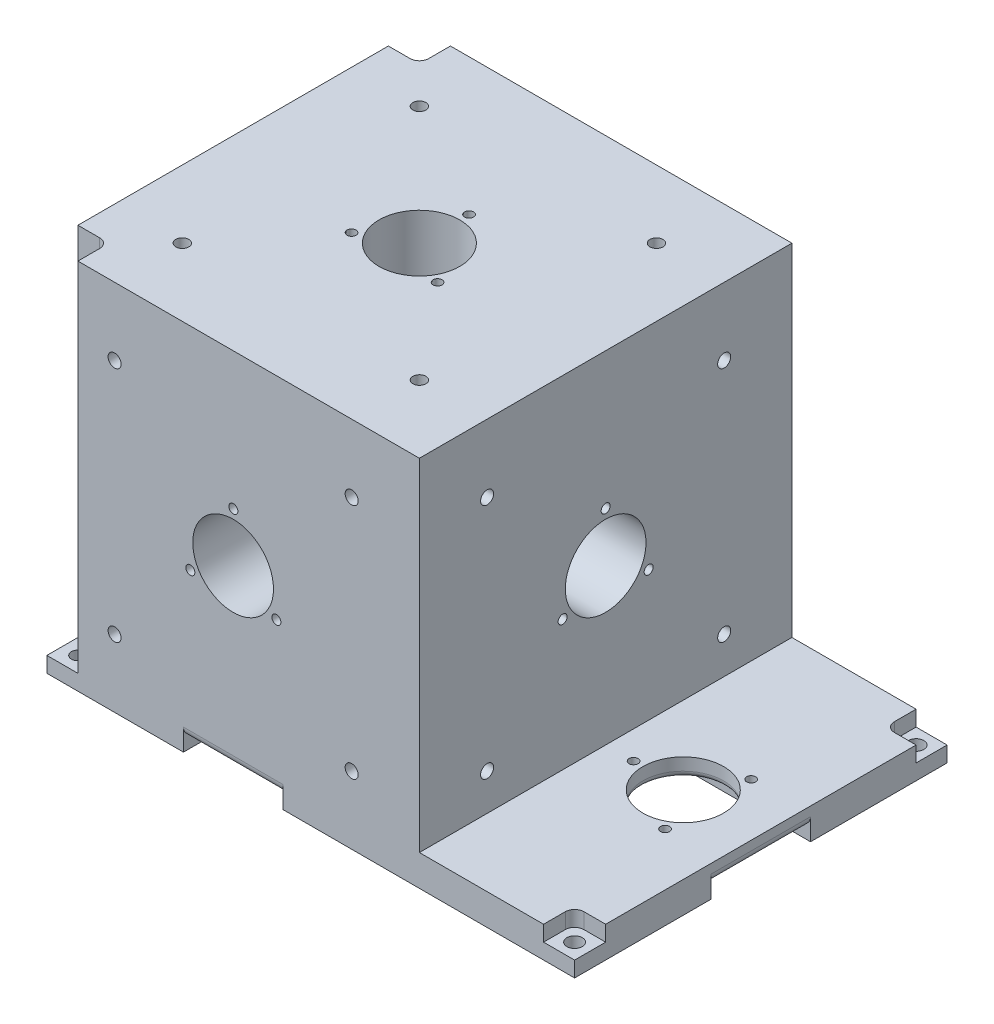
SolidWorks part; units mm, degrees
ref_plane "Front Plane" through (0, 0, 0) normal (0, 0, 1) x (1, 0, 0)
ref_plane "Top Plane" through (0, 0, 0) normal (0, 1, 0) x (1, 0, 0)
ref_plane "Right Plane" through (0, 0, 0) normal (1, 0, 0) x (0, 0, -1)
sketch "Sketch1" plane through (0, 0, 0) normal (0, 1, 0) x (1, 0, 0)
  line L0 (-60, 60) -> (-60, -60)
  line L1 (0, 60) -> (-60, 60)
  line L2 (0, 60) -> (60, 60)
  line L3 (-60, -60) -> (60, -60)
  line L4 (60, 60) -> (60, -60)
extrude "Boss-Extrude1" add sketch "Sketch1" along normal blind 120 contours L1 L0 L3 L4 L2
sketch "Sketch3" plane through (60, 0, 0) normal (1, 0, 0) x (0, 0, -1)
  line L0 (-60, 0) -> (-60, 10)
  line L1 (-60, 120) -> (-60, 0) construction
  line L2 (-60, 10) -> (60, 10)
  line L3 (60, 120) -> (60, 0) construction
  line L4 (60, 10) -> (60, 0)
  line L5 (60, 0) -> (-60, 0)
extrude "Boss-Extrude2" add sketch "Sketch3" along normal blind 50
sketch "Sketch4" plane through (0, 0, 0) normal (0, -1, 0) x (1, 0, 0)
  line L0 (16, 16) -> (110, 16)
  line L1 (16, -16) -> (110, -16)
  line L2 (110, -16) -> (110, 16)
  line L3 (-16, -16) -> (-16, -60)
  line L4 (110, -60) -> (-60, -60) construction
  line L5 (-16, 16) -> (-16, 60)
  line L6 (-60, 60) -> (110, 60) construction
  line L7 (16, -16) -> (16, -60)
  line L8 (16, 16) -> (16, 60)
  line L9 (-16, 16) -> (-60, 16)
  line L10 (-60, -60) -> (-60, 60) construction
  line L11 (-16, -16) -> (-60, -16)
  line L12 (16, -60) -> (-16, -60)
  line L13 (-60, -16) -> (-60, 16)
  line L14 (16, 60) -> (-16, 60)
sketch "Sketch7" plane through (-60, 0, 0) normal (-1, 0, 0) x (0, 0, 1)
  circle A0 centre (0, 60) radius 13
  circle A1 centre (0, 76) radius 1.75
  circle A2 centre (13.8564, 52) radius 1.75
  circle A3 centre (-13.8564, 52) radius 1.75
  circle A7 centre (-38.1838, 98.1838) radius 2
  circle A8 centre (38.1838, 98.1838) radius 2
  circle A9 centre (38.1838, 21.8162) radius 2
  circle A10 centre (-38.1838, 21.8162) radius 2
  point P2 (-38.1838, 98.1838)
  point P10 (0, 60)
  point P14 (0, 60)
  point P18 (0, 60)
  dimension "D1" = 3
sketch "Sketch8" plane through (0, 0, -60) normal (0, 0, -1) x (-1, 0, 0)
  circle A0 centre (0, 60) radius 13
  circle A1 centre (0, 76) radius 1.825
  circle A2 centre (13.8564, 52) radius 1.825
  circle A3 centre (-13.8564, 52) radius 1.825
  circle A7 centre (-38.1838, 98.1838) radius 2
  circle A8 centre (38.1838, 98.1838) radius 2
  circle A9 centre (38.1838, 21.8162) radius 2
  circle A10 centre (-38.1838, 21.8162) radius 2
  point P0 (-38.1838, 98.1838)
  point P13 (0, 60)
  point P17 (0, 60)
  point P18 (0, 60)
sketch "Sketch10" plane through (0, 120, 0) normal (0, 1, 0) x (1, 0, 0)
  circle A0 centre (0, 0) radius 13
  circle A1 centre (0, 16) radius 1.825
  circle A2 centre (13.8564, -8) radius 1.825
  circle A3 centre (-13.8564, -8) radius 1.825
  point P10 (0, 0)
  point P14 (0, 0)
sketch "Sketch11" plane through (0, 0, 60) normal (0, 0, 1) x (1, 0, 0)
  line L0 (0, 0) -> (0, 120)
  line L1 (-60, 120) -> (60, 120) construction
  circle A4 centre (0, 60) radius 13
  circle A5 centre (0, 76) radius 1.825
  circle A6 centre (13.8564, 52) radius 1.825
  circle A7 centre (-13.8564, 52) radius 1.825
  point P10 (0, 60)
  point P14 (0, 60)
sketch "Sketch13" plane through (60, 0, 0) normal (1, 0, 0) x (0, 0, -1)
  circle A0 centre (0, 60) radius 13
  circle A1 centre (0, 76) radius 1.825
  circle A2 centre (13.8564, 52) radius 1.825
  circle A3 centre (-13.8564, 52) radius 1.825
  point P5 (0, 60)
  point P9 (0, 60)
extrude "Cut-Extrude3" cut sketch "Sketch11" against normal blind 120 contours A4
extrude "Cut-Extrude12" cut sketch "Sketch4" against normal blind 4 contours L1 L2 L0 L8 L14 L5 L9 L13 L11 L3 L12 L7
extrude "Cut-Extrude13" cut sketch "Sketch10" against normal blind 116 contours A0
extrude "Cut-Extrude17" cut sketch "Sketch13" against normal blind 120 contours A0
sketch "Sketch17" plane through (0, 10, 0) normal (0, 1, 0) x (1, 0, 0)
  circle A0 centre (85, 0) radius 13
extrude "Cut-Extrude18" cut sketch "Sketch17" against normal blind 6 contours A0
sketch "Sketch18" plane through (0, 10, 0) normal (0, 1, 0) x (1, 0, 0)
  line L0 (110, 0) -> (60, 0)
  line L1 (110, 60) -> (110, -60) construction
  line L2 (60, 60) -> (60, -60) construction
  line L3 (85, 0) -> (69, 0)
  circle A0 centre (93, 13.8564) radius 1.75
  circle A1 centre (69, 0) radius 1.75
  circle A2 centre (93, -13.8564) radius 1.75
  point P16 (85, 0)
  dimension "D1" = 3
fillet "Fillet1" radius 3 4 edges at (16, 2, 16) (-16, 2, 16) (-16, 2, -16) (16, 2, -16)
fillet "Fillet2" radius 3 1 edges at (0, 4, 13)
sketch "Sketch19" plane through (0, 120, 0) normal (0, 1, 0) x (1, 0, 0)
  line L0 (-60, 60) -> (-50, 60)
  line L3 (-60, 60) -> (-60, -60) construction
  line L4 (-60, 50) -> (-60, 60)
  line L5 (-60, -50) -> (-50, -50)
  line L6 (-50, -50) -> (-50, -60)
  line L7 (-50, -60) -> (-60, -60)
  line L8 (-60, -60) -> (-60, -50)
  line L9 (-60, -60) -> (-55, -60)
  line L10 (-60, -60) -> (60, -60) construction
  line L11 (-50, 60) -> (-50, 50)
  line L12 (-50, 50) -> (-60, 50)
extrude "Cut-Extrude20" cut sketch "Sketch19" against normal blind 115 contours L12 L4 L0 L11 | L5 L6 L7 L8
sketch "Sketch20" plane through (0, 5, 0) normal (0, 1, 0) x (1, 0, 0)
  circle A0 centre (-55, 55) radius 2.5
  circle A1 centre (-55, -55) radius 2.5
fillet "Fillet3" radius 3 2 edges at (-50, 62.5, 50) (-50, 62.5, -50)
sketch "Sketch21" plane through (0, 10, 0) normal (0, 1, 0) x (1, 0, 0)
  line L0 (110, -60) -> (100, -60)
  line L1 (110, -60) -> (60, -60) construction
  line L2 (100, -60) -> (100, -50)
  line L3 (100, -50) -> (110, -50)
  line L4 (110, 60) -> (110, -60) construction
  line L5 (110, -50) -> (110, -60)
  line L6 (110, 50) -> (100, 50)
  line L7 (100, 50) -> (100, 60)
  line L8 (100, 60) -> (110, 60)
  line L9 (110, 60) -> (110, 50)
  line L10 (110, 60) -> (95, 60)
  line L11 (110, 60) -> (60, 60) construction
extrude "Cut-Extrude22" cut sketch "Sketch21" against normal blind 5 contours L3 L2 L5 L10 | L7 L6 L10 L11
sketch "Sketch22" plane through (0, 5, 0) normal (0, 1, 0) x (1, 0, 0)
  circle A0 centre (105, 55) radius 2.5
  circle A1 centre (105, -55) radius 2.5
fillet "Fillet4" radius 3 2 edges at (100, 7.5, -50) (100, 7.5, 50)
sketch "Sketch23" plane through (0, 0, 60) normal (0, 0, 1) x (1, 0, 0)
  circle A0 centre (0.0779, 75.9221) radius 1.825
  circle A1 centre (13.9343, 51.9221) radius 1.825
  circle A2 centre (-13.7785, 51.9221) radius 1.825
  circle A3 centre (-38.1838, 98.1838) radius 2
  circle A4 centre (38.1838, 98.1838) radius 2
  circle A5 centre (38.1838, 21.8162) radius 2
  circle A6 centre (-38.1838, 21.8162) radius 2
  point P0 (-38.1838, 98.1838)
  point P8 (0, 60)
  point P10 (0.0779, 59.9221)
  point P17 (0, 60)
sketch "Sketch24" plane through (60, 0, 0) normal (1, 0, 0) x (0, 0, -1)
  circle A9 centre (0, 76) radius 1.825
  circle A10 centre (13.8564, 52) radius 1.825
  circle A11 centre (-13.8564, 52) radius 1.825
  circle A12 centre (-38.1838, 98.1838) radius 2
  circle A13 centre (38.1838, 98.1838) radius 2
  circle A14 centre (38.1838, 21.8162) radius 2
  circle A15 centre (-38.1838, 21.8162) radius 2
  point P2 (-38.1838, 98.1838)
  point P8 (0, 60)
  point P12 (0, 60)
  point P13 (0, 60)
sketch "Sketch26" plane through (0, 120, 0) normal (0, 1, 0) x (1, 0, 0)
  circle A1 centre (0, 16) radius 1.825
  circle A2 centre (13.8564, -8) radius 1.825
  circle A3 centre (-13.8564, -8) radius 1.825
  circle A4 centre (-38.1838, 38.1838) radius 2
  circle A5 centre (38.1838, 38.1838) radius 2
  circle A6 centre (38.1838, -38.1838) radius 2
  circle A7 centre (-38.1838, -38.1838) radius 2
  point P2 (-38.1838, 38.1838)
  point P8 (0, 0)
  point P12 (0, 0)
  point P13 (0, 0)
hole_wizard "M3.5 Tapped Hole1" positions "Sketch34" profile "Sketch36" tap size "M3.5" standard "ISO"
sketch "Sketch34" plane through (-60, 0, 0) normal (-1, 0, 0) x (0, 0, 1)
  point P0 (0, 76)
  point P3 (-13.8564, 52)
  point P6 (13.8564, 52)
cosmetic thread "Hole Thread1" parameters "D1"=4, "D2"=3.5
cosmetic thread "Hole Thread2" parameters "D1"=4, "D2"=3.5
cosmetic thread "Hole Thread3" parameters "D1"=4, "D2"=3.5
sketch "Sketch36" plane through (-60, 76, 0) normal (0, 1, 0) x (0, 0, 1)
  line L0 (0, 0) -> (0, 5.8712)
  line L1 (0, 5.8712) -> (1.45, 5)
  line L2 (1.45, 5) -> (1.45, 0)
  line L5 (1.45, 0) -> (0, 0)
  line L10 (0, 5.8712) -> (-1.45, 5) construction
  line L11 (0, -6.35) -> (0, 107.95) construction
  dimension "Tap Drill Dia." = 2.9
  dimension "Tap Drill Depth" = 5
  dimension "Drill Angle" = 118
hole_wizard "M5 Tapped Hole1" positions "Sketch42" profile "Sketch43" tap size "M5" standard "ISO"
sketch "Sketch42" plane through (60, 0, 0) normal (1, 0, 0) x (0, 0, -1)
  point P0 (-38.1838, 21.8162)
  point P3 (38.1838, 21.8162)
  point P6 (38.1838, 98.1838)
  point P9 (-38.1838, 98.1838)
sketch "Sketch43" plane through (60, 21.8162, 38.1838) normal (0, 1, 0) x (0, 0, -1)
  line L0 (0, 0) -> (0, 5.7618)
  line L1 (0, 5.7618) -> (2.1, 4.5)
  line L2 (2.1, 4.5) -> (2.1, 0)
  line L5 (2.1, 0) -> (0, 0)
  line L10 (0, 5.7618) -> (-2.1, 4.5) construction
  line L11 (0, -6.35) -> (0, 107.95) construction
  dimension "Tap Drill Dia." = 4.2
  dimension "Tap Drill Depth" = 4.5
  dimension "Drill Angle" = 118
cosmetic thread "Hole Thread4" parameters "D1"=3.9, "D2"=5
cosmetic thread "Hole Thread5" parameters "D1"=3.9, "D2"=5
cosmetic thread "Hole Thread6" parameters "D1"=3.9, "D2"=5
cosmetic thread "Hole Thread7" parameters "D1"=3.9, "D2"=5
hole_wizard "M5 Tapped Hole2" positions "Sketch44" profile "Sketch45" tap size "M5" standard "ISO"
sketch "Sketch44" plane through (-60, 0, 0) normal (-1, 0, 0) x (0, 0, 1)
  point P0 (-38.1838, 98.1838)
  point P3 (38.1838, 98.1838)
  point P6 (-38.1838, 21.8162)
  point P9 (38.1838, 21.8162)
sketch "Sketch45" plane through (-60, 98.1838, -38.1838) normal (0, 1, 0) x (0, 0, 1)
  line L0 (0, 0) -> (0, 5.7618)
  line L1 (0, 5.7618) -> (2.1, 4.5)
  line L2 (2.1, 4.5) -> (2.1, 0)
  line L5 (2.1, 0) -> (0, 0)
  line L10 (0, 5.7618) -> (-2.1, 4.5) construction
  line L11 (0, -6.35) -> (0, 107.95) construction
  dimension "Tap Drill Dia." = 4.2
  dimension "Tap Drill Depth" = 4.5
  dimension "Drill Angle" = 118
cosmetic thread "Hole Thread8" parameters "D1"=3.9, "D2"=5
cosmetic thread "Hole Thread9" parameters "D1"=3.9, "D2"=5
cosmetic thread "Hole Thread10" parameters "D1"=3.9, "D2"=5
cosmetic thread "Hole Thread11" parameters "D1"=3.9, "D2"=5
fillet "Fillet5" radius 3 4 edges at (110, 4, 0) (0, 4, 60) (-60, 4, 0) (0, 4, -60)
hole_wizard "M5 Tapped Hole3" positions "Sketch46" profile "Sketch47" tap size "M5" standard "ISO"
sketch "Sketch46" plane through (0, 0, -60) normal (0, 0, -1) x (-1, 0, 0)
  point P0 (-38.1838, 98.1838)
  point P3 (38.1838, 98.1838)
  point P6 (38.1838, 21.8162)
  point P9 (-38.1838, 21.8162)
sketch "Sketch47" plane through (38.1838, 98.1838, -60) normal (1, 0, 0) x (0, 1, 0)
  line L0 (0, 0) -> (0, 5.7618)
  line L1 (0, 5.7618) -> (2.1, 4.5)
  line L2 (2.1, 4.5) -> (2.1, 0)
  line L5 (2.1, 0) -> (0, 0)
  line L10 (0, 5.7618) -> (-2.1, 4.5) construction
  line L11 (0, -6.35) -> (0, 107.95) construction
  dimension "Tap Drill Dia." = 4.2
  dimension "Tap Drill Depth" = 4.5
  dimension "Drill Angle" = 118
cosmetic thread "Hole Thread12" parameters "D1"=3.7, "D2"=5
cosmetic thread "Hole Thread13" parameters "D1"=3.7, "D2"=5
cosmetic thread "Hole Thread14" parameters "D1"=3.7, "D2"=5
cosmetic thread "Hole Thread15" parameters "D1"=3.7, "D2"=5
hole_wizard "M3.5 Tapped Hole2" positions "Sketch48" profile "Sketch49" tap size "M3.5" standard "ISO"
sketch "Sketch48" plane through (0, 0, -60) normal (0, 0, -1) x (-1, 0, 0)
  point P0 (-13.8564, 52)
  point P3 (0, 76)
  point P6 (13.8564, 52)
sketch "Sketch49" plane through (13.8564, 52, -60) normal (1, 0, 0) x (0, 1, 0)
  line L0 (0, 0) -> (0, 5.8712)
  line L1 (0, 5.8712) -> (1.45, 5)
  line L2 (1.45, 5) -> (1.45, 0)
  line L5 (1.45, 0) -> (0, 0)
  line L10 (0, 5.8712) -> (-1.45, 5) construction
  line L11 (0, -6.35) -> (0, 107.95) construction
  dimension "Tap Drill Dia." = 2.9
  dimension "Tap Drill Depth" = 5
  dimension "Drill Angle" = 118
cosmetic thread "Hole Thread16" parameters "D1"=5, "D2"=3.5
cosmetic thread "Hole Thread17" parameters "D1"=5, "D2"=3.5
cosmetic thread "Hole Thread18" parameters "D1"=5, "D2"=3.5
hole_wizard "M3.5 Tapped Hole3" positions "Sketch52" profile "Sketch53" tap size "M3.5" standard "ISO"
sketch "Sketch52" plane through (0, 120, 0) normal (0, 1, 0) x (1, 0, 0)
  point P0 (0, 16)
  point P3 (13.8564, -8)
  point P6 (-13.8564, -8)
sketch "Sketch53" plane through (0, 120, -16) normal (1, 0, 0) x (0, 0, 1)
  line L0 (0, 0) -> (0, 5.8712)
  line L1 (0, 5.8712) -> (1.45, 5)
  line L2 (1.45, 5) -> (1.45, 0)
  line L5 (1.45, 0) -> (0, 0)
  line L10 (0, 5.8712) -> (-1.45, 5) construction
  line L11 (0, -6.35) -> (0, 107.95) construction
  dimension "Tap Drill Dia." = 2.9
  dimension "Tap Drill Depth" = 5
  dimension "Drill Angle" = 118
cosmetic thread "Hole Thread19" parameters "D1"=4.4, "D2"=3.5
cosmetic thread "Hole Thread20" parameters "D1"=4.4, "D2"=3.5
cosmetic thread "Hole Thread21" parameters "D1"=4.4, "D2"=3.5
hole_wizard "M5 Tapped Hole4" positions "Sketch56" profile "Sketch55" tap size "M5" standard "ISO"
sketch "Sketch56" plane through (0, 120, 0) normal (0, 1, 0) x (1, 0, 0)
  point P0 (38.1838, 38.1838)
  point P3 (38.1838, -38.1838)
  point P6 (-38.1838, -38.1838)
  point P9 (-38.1838, 38.1838)
sketch "Sketch55" plane through (38.1838, 120, -38.1838) normal (1, 0, 0) x (0, 0, 1)
  line L0 (0, 0) -> (0, 5.7618)
  line L1 (0, 5.7618) -> (2.1, 4.5)
  line L2 (2.1, 4.5) -> (2.1, 0)
  line L5 (2.1, 0) -> (0, 0)
  line L10 (0, 5.7618) -> (-2.1, 4.5) construction
  line L11 (0, -6.35) -> (0, 107.95) construction
  dimension "Tap Drill Dia." = 4.2
  dimension "Tap Drill Depth" = 4.5
  dimension "Drill Angle" = 118
cosmetic thread "Hole Thread22" parameters "D1"=4.4, "D2"=5
cosmetic thread "Hole Thread23" parameters "D1"=4.4, "D2"=5
cosmetic thread "Hole Thread24" parameters "D1"=4.4, "D2"=5
cosmetic thread "Hole Thread25" parameters "D1"=4.4, "D2"=5
hole_wizard "M3.5 Tapped Hole5" positions "Sketch57" profile "Sketch58" tap size "M3.5" standard "ISO"
sketch "Sketch57" plane through (60, 0, 0) normal (1, 0, 0) x (0, 0, -1)
  point P0 (-13.8564, 52)
  point P3 (13.8564, 52)
  point P6 (0, 76)
sketch "Sketch58" plane through (60, 52, 13.8564) normal (0, 1, 0) x (0, 0, -1)
  line L0 (0, 0) -> (0, 5.8712)
  line L1 (0, 5.8712) -> (1.45, 5)
  line L2 (1.45, 5) -> (1.45, 0)
  line L5 (1.45, 0) -> (0, 0)
  line L10 (0, 5.8712) -> (-1.45, 5) construction
  line L11 (0, -6.35) -> (0, 107.95) construction
  dimension "Tap Drill Dia." = 2.9
  dimension "Tap Drill Depth" = 5
  dimension "Drill Angle" = 118
cosmetic thread "Hole Thread26" parameters "D1"=4.4, "D2"=3.5
cosmetic thread "Hole Thread27" parameters "D1"=4.4, "D2"=3.5
cosmetic thread "Hole Thread28" parameters "D1"=4.4, "D2"=3.5
hole_wizard "M3.5 Tapped Hole6" positions "Sketch59" profile "Sketch60" tap size "M3.5" standard "ISO"
sketch "Sketch59" plane through (0, 0, 60) normal (0, 0, 1) x (1, 0, 0)
  point P0 (0.0779, 75.9221)
  point P3 (13.9343, 51.9221)
  point P6 (-13.7785, 51.9221)
sketch "Sketch60" plane through (0.0779, 75.9221, 60) normal (1, 0, 0) x (0, -1, 0)
  line L0 (0, 0) -> (0, 5.8712)
  line L1 (0, 5.8712) -> (1.45, 5)
  line L2 (1.45, 5) -> (1.45, 0)
  line L5 (1.45, 0) -> (0, 0)
  line L10 (0, 5.8712) -> (-1.45, 5) construction
  line L11 (0, -6.35) -> (0, 107.95) construction
  dimension "Tap Drill Dia." = 2.9
  dimension "Tap Drill Depth" = 5
  dimension "Drill Angle" = 118
cosmetic thread "Hole Thread29" parameters "D1"=4.4, "D2"=3.5
cosmetic thread "Hole Thread30" parameters "D1"=4.4, "D2"=3.5
cosmetic thread "Hole Thread31" parameters "D1"=4.4, "D2"=3.5
hole_wizard "M5 Tapped Hole5" positions "Sketch61" profile "Sketch62" tap size "M5" standard "ISO"
sketch "Sketch61" plane through (0, 0, 60) normal (0, 0, 1) x (1, 0, 0)
  point P0 (-38.1838, 98.1838)
  point P3 (38.1838, 98.1838)
  point P6 (38.1838, 21.8162)
  point P9 (-38.1838, 21.8162)
sketch "Sketch62" plane through (-38.1838, 98.1838, 60) normal (1, 0, 0) x (0, -1, 0)
  line L0 (0, 0) -> (0, 5.7618)
  line L1 (0, 5.7618) -> (2.1, 4.5)
  line L2 (2.1, 4.5) -> (2.1, 0)
  line L5 (2.1, 0) -> (0, 0)
  line L10 (0, 5.7618) -> (-2.1, 4.5) construction
  line L11 (0, -6.35) -> (0, 107.95) construction
  dimension "Tap Drill Dia." = 4.2
  dimension "Tap Drill Depth" = 4.5
  dimension "Drill Angle" = 118
cosmetic thread "Hole Thread32" parameters "D1"=3.7, "D2"=5
cosmetic thread "Hole Thread33" parameters "D1"=3.7, "D2"=5
cosmetic thread "Hole Thread34" parameters "D1"=3.7, "D2"=5
cosmetic thread "Hole Thread35" parameters "D1"=3.7, "D2"=5
hole_wizard "M3.5 Tapped Hole7" positions "Sketch63" profile "Sketch64" tap size "M3.5" standard "ISO"
sketch "Sketch63" plane through (0, 10, 0) normal (0, 1, 0) x (1, 0, 0)
  point P0 (93, -13.8564)
  point P3 (69, 0)
  point P6 (93, 13.8564)
sketch "Sketch64" plane through (93, 10, 13.8564) normal (1, 0, 0) x (0, 0, 1)
  line L0 (0, 0) -> (0, 5.8712)
  line L1 (0, 5.8712) -> (1.45, 5)
  line L2 (1.45, 5) -> (1.45, 0)
  line L5 (1.45, 0) -> (0, 0)
  line L10 (0, 5.8712) -> (-1.45, 5) construction
  line L11 (0, -6.35) -> (0, 107.95) construction
  dimension "Tap Drill Dia." = 2.9
  dimension "Tap Drill Depth" = 5
  dimension "Drill Angle" = 118
cosmetic thread "Hole Thread36" parameters "D1"=4.4, "D2"=3.5
cosmetic thread "Hole Thread37" parameters "D1"=4.4, "D2"=3.5
cosmetic thread "Hole Thread38" parameters "D1"=4.4, "D2"=3.5
hole_wizard "M6 Tapped Hole1" positions "Sketch65" profile "Sketch67" tap size "M6" standard "ISO" end condition up to next
sketch "Sketch65" plane through (0, 5, 0) normal (0, 1, 0) x (1, 0, 0)
  point P0 (105, -55)
  point P3 (105, 55)
sketch "Sketch67" plane through (105, 5, 55) normal (1, 0, 0) x (0, 0, 1)
  line L0 (0, 0) -> (0, 5)
  line L1 (0, 5) -> (2.5, 5)
  line L2 (2.5, 5) -> (2.5, 0)
  line L5 (2.5, 0) -> (0, 0)
  line L11 (0, -6.35) -> (0, 107.95) construction
  dimension "Thru Tap Drill Dia." = 5
  dimension "Thru Tap Drill Depth" = 5
cosmetic thread "Hole Thread39" parameters "D2"=6
cosmetic thread "Hole Thread40" parameters "D2"=6
hole_wizard "M5 Tapped Hole7" positions "Sketch70" profile "Sketch71" tap size "M5" standard "ISO" end condition through all
sketch "Sketch70" plane through (0, 5, 0) normal (0, 1, 0) x (1, 0, 0)
  point P0 (-55, 55)
  point P3 (-55, -55)
cosmetic thread "Hole Thread43" parameters "D2"=5
cosmetic thread "Hole Thread44" parameters "D2"=5
sketch "Sketch71" plane through (-55, 5, -55) normal (1, 0, 0) x (0, 0, 1)
  line L0 (0, 0) -> (0, 5)
  line L1 (0, 5) -> (2.1, 5)
  line L2 (2.1, 5) -> (2.1, 0)
  line L5 (2.1, 0) -> (0, 0)
  line L11 (0, -6.35) -> (0, 107.95) construction
  dimension "Thru Tap Drill Dia." = 4.2
  dimension "Thru Tap Drill Depth" = 5
fillet "Fillet6" radius 2 1 edges at (85, 4, 13)
